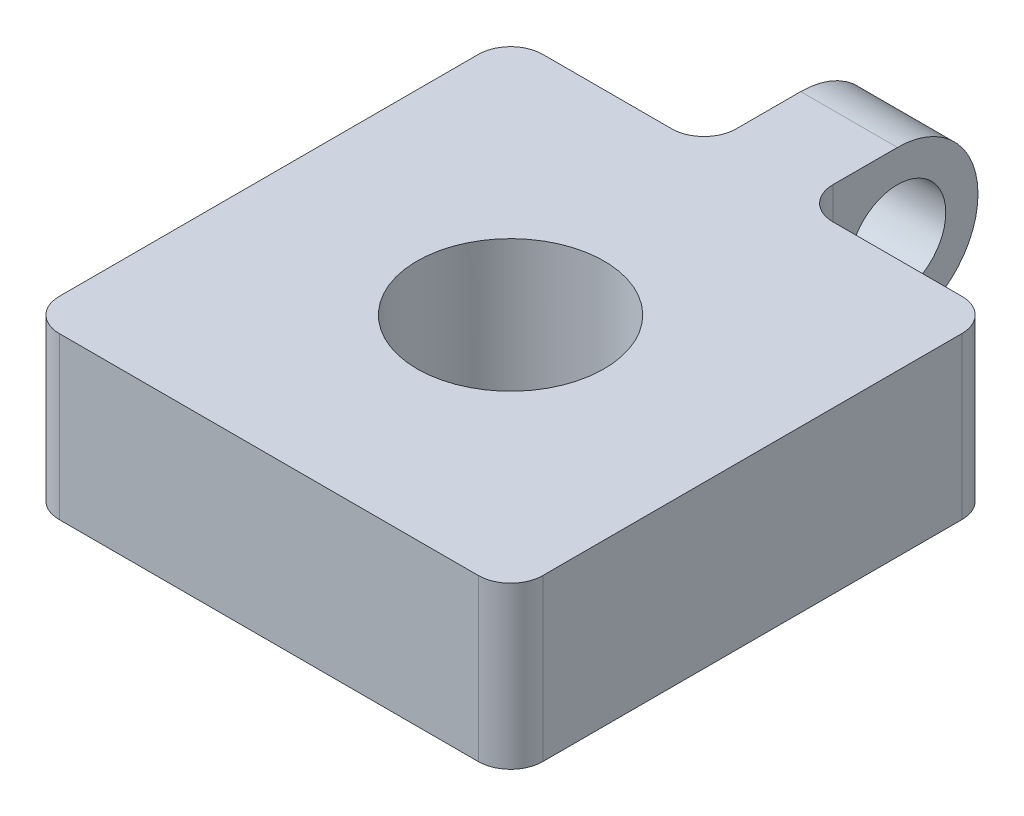
SolidWorks part; units mm, degrees
ref_plane "Front Plane" through (0, 0, 0) normal (0, 0, 1) x (1, 0, 0)
ref_plane "Top Plane" through (0, 0, 0) normal (0, 1, 0) x (1, 0, 0)
ref_plane "Right Plane" through (0, 0, 0) normal (1, 0, 0) x (0, 0, -1)
sketch "Sketch1" plane through (0, 0, 0) normal (0, 1, 0) x (1, 0, 0)
  line L1 (-7.5, -7.5) -> (7.5, -7.5)
  line L2 (-7.5, -7.5) -> (-7.5, 7.5)
  line L3 (-7.5, 7.5) -> (7.5, 7.5)
  line L4 (7.5, -7.5) -> (7.5, 7.5)
  line L5 (-7.5, -7.5) -> (7.5, 7.5) construction
  line L6 (-7.5, 7.5) -> (7.5, -7.5) construction
  point P0 (0, 0)
  dimension "D1" = 15
  dimension "D2" = 15
extrude "Boss-Extrude1" add sketch "Sketch1" along normal blind 5
sketch "Sketch3" plane through (0, 0, 0) normal (1, 0, 0) x (0, 0, -1)
  line L0 (7.5, 5) -> (10.5, 5)
  line L1 (7.5, 0) -> (10.5, 0)
  line L2 (7.5, 5) -> (7.5, 0)
  arc A0 (10.5, 5) -> (10.5, 0) centre (10.5, 2.5) cw
  circle A1 centre (10.5, 2.5) radius 1.5
  dimension "D2" = 3
  dimension "D1" = 3
extrude "Boss-Extrude2" add sketch "Sketch3" along normal mid plane 3
sketch "Sketch4" plane through (0, 5, 0) normal (0, 1, 0) x (1, 0, 0)
  circle A0 centre (0, 0) radius 2.9
  dimension "D1" = 5.8
extrude "Cut-Extrude1" cut sketch "Sketch4" against normal up to next
fillet "Fillet1" radius 1 6 edges at (-7.5, 2.5, -7.5) (-7.5, 2.5, 7.5) (7.5, 2.5, 7.5) (7.5, 2.5, -7.5) (1.5, 2.5, -7.5) (-1.5, 2.5, -7.5)
